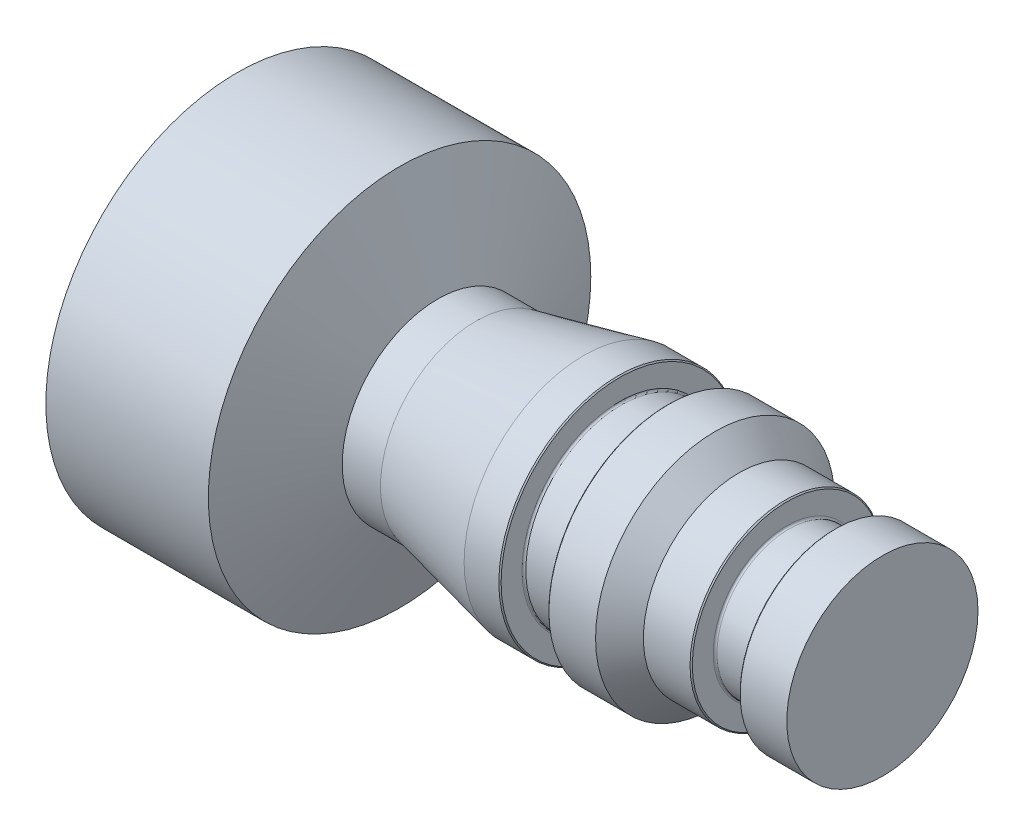
SolidWorks part; units mm, degrees
ref_plane "Plane1" through (0, 0, 0) normal (0, 0, 1) x (1, 0, 0)
ref_plane "Plane2" through (0, 0, 0) normal (0, 1, 0) x (1, 0, 0)
ref_plane "Plane3" through (0, 0, 0) normal (1, 0, 0) x (0, 0, -1)
sketch "Sketch1" plane through (0, 0, 0) normal (0, 0, 1) x (1, 0, 0)
  line L0 (0, 0) -> (0, 25.4)
  line L2 (0, 25.4) -> (-12.7, 25.4)
  line L3 (-38.1, 25.4) -> (-44.45, 31.75)
  line L4 (-44.45, 31.75) -> (-57.15, 31.75)
  line L5 (-79.375, 31.75) -> (-107.95, 25.4)
  line L6 (-107.95, 25.4) -> (-118.11, 25.4)
  line L7 (-118.11, 25.4) -> (-128.27, 50.8)
  line L8 (-128.27, 50.8) -> (-171.45, 50.8)
  line L9 (-171.45, 50.8) -> (-171.45, 0)
  line L10 (0, 0) -> (-171.45, 0)
  line L11 (0, 0) -> (-184.15, 0) construction
  line L12 (-25.4, 25.4) -> (-38.1, 25.4)
  line L13 (-25.4, 25.4) -> (-25.4, 19.558)
  line L14 (-13.208, 19.05) -> (-24.892, 19.05)
  line L15 (-12.7, 19.558) -> (-12.7, 25.4)
  line L16 (-69.85, 31.75) -> (-79.375, 31.75)
  line L17 (-69.85, 31.75) -> (-69.85, 25.908)
  line L18 (-57.658, 25.4) -> (-69.342, 25.4)
  line L19 (-57.15, 25.908) -> (-57.15, 31.75)
  arc A0 (-12.7, 19.558) -> (-13.208, 19.05) centre (-13.208, 19.558) cw
  arc A1 (-25.4, 19.558) -> (-24.892, 19.05) centre (-24.892, 19.558) ccw
  arc A2 (-57.15, 25.908) -> (-57.658, 25.4) centre (-57.658, 25.908) cw
  arc A3 (-69.342, 25.4) -> (-69.85, 25.908) centre (-69.342, 25.908) cw
  dimension "D1" = 0.508
revolve "Base-Revolve" add sketch "Sketch1" angle 360 about L11
chamfer "Chamfer1" distance 0.3048 angle 45
